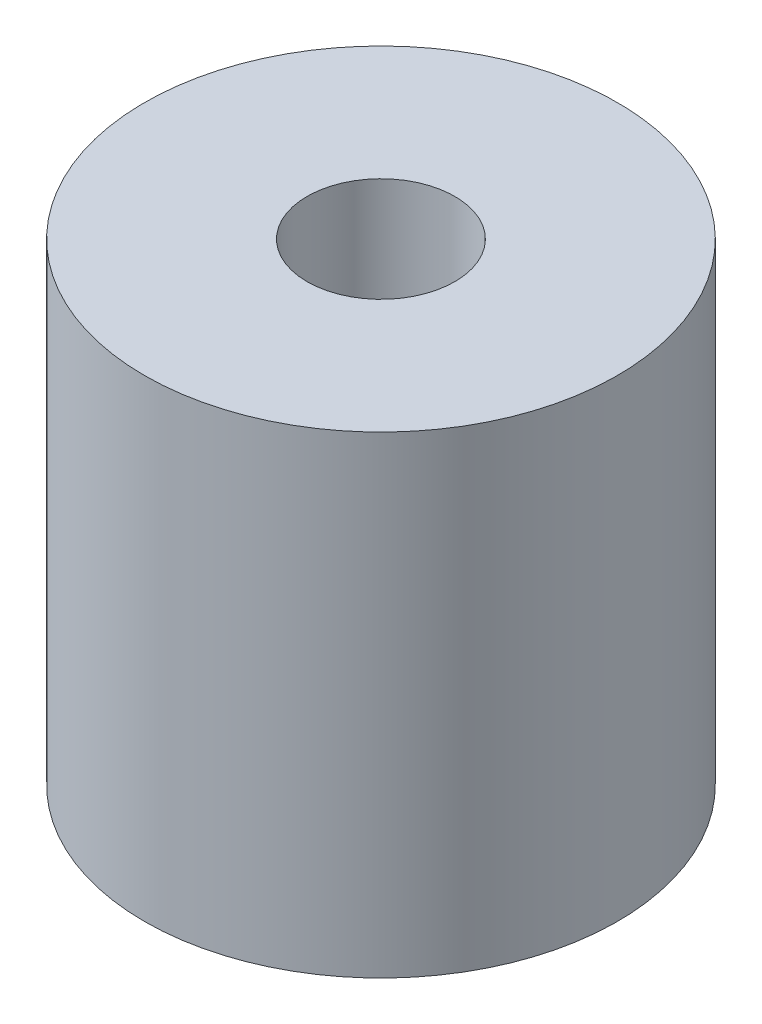
SolidWorks part; units mm, degrees
ref_plane "Front Plane" through (0, 0, 0) normal (0, 0, 1) x (1, 0, 0)
ref_plane "Top Plane" through (0, 0, 0) normal (0, 1, 0) x (1, 0, 0)
ref_plane "Right Plane" through (0, 0, 0) normal (1, 0, 0) x (0, 0, -1)
sketch "Sketch1" plane through (0, 0, 0) normal (0, 1, 0) x (1, 0, 0)
  circle A0 centre (0, 0) radius 2.5
  circle A1 centre (0, 0) radius 8
extrude "Boss-Extrude1" add sketch "Sketch1" along normal blind 16
